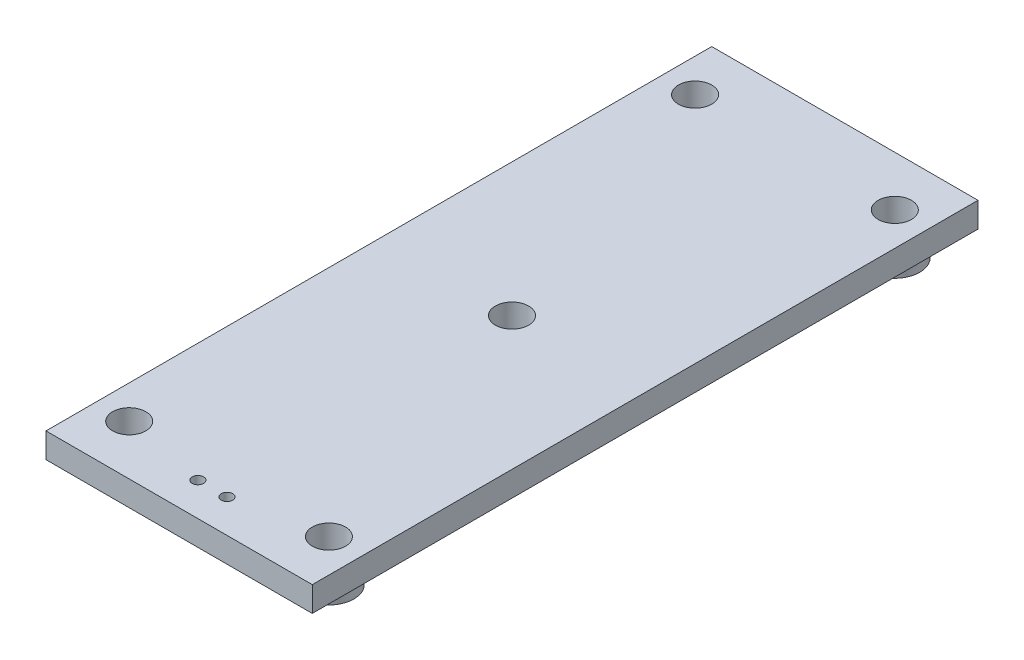
SolidWorks part; units mm, degrees
material "PW50:3:Ar:0:-1:C1:1:2:3:Re:11:"
ref_plane "front" through (0, 0, 0) normal (0, 0, 1) x (1, 0, 0)
ref_plane "top" through (0, 0, 0) normal (0, 1, 0) x (1, 0, 0)
ref_plane "side" through (0, 0, 0) normal (1, 0, 0) x (0, 0, -1)
sketch "Sketch1" plane through (0, 0, 0) normal (0, 1, 0) x (1, 0, 0)
  line L0 (101.6, 0) -> (-101.6, 0)
  line L1 (101.6, 0) -> (101.6, -508)
  line L2 (-101.6, -508) -> (101.6, -508)
  line L3 (-101.6, -508) -> (-101.6, 0)
  line L4 (0, 0) -> (0, -508) construction
  dimension "D1" = 508
  dimension "D2" = 203.2
extrude "Base-Extrude" add sketch "Sketch1" along normal blind 19.05
sketch "Sketch2" plane through (0, 0, 0) normal (0, -1, 0) x (1, 0, 0)
  line L0 (0, 508) -> (0, 254) construction
  line L1 (-101.6, 508) -> (101.6, 508) construction
  line L2 (101.6, 254) -> (0, 254) construction
  line L3 (101.6, 0) -> (101.6, 508) construction
  circle A0 centre (76.2, 469.9) radius 19.05
  circle A1 centre (76.2, 38.1) radius 19.05
  circle A2 centre (-76.2, 38.1) radius 19.05
  circle A3 centre (-76.2, 469.9) radius 19.05
  dimension "D2" = 38.1
  dimension "D1" = 38.1
  dimension "D3" = 152.4
extrude "Boss-Extrude1" add sketch "Sketch2" along normal blind 12.7
sketch "Sketch3" plane through (0, -12.7, 0) normal (0, -1, 0) x (1, 0, 0)
  circle A0 centre (76.2, 469.9) radius 12.7
  circle A2 centre (-76.2, 469.9) radius 12.7
  circle A3 centre (76.2, 38.1) radius 12.7
  circle A4 centre (-76.2, 38.1) radius 12.7
  circle A5 centre (-76.2, 38.1) radius 19.05 construction
  circle A6 centre (76.2, 38.1) radius 19.05 construction
  dimension "D1" = 25.4
extrude "Cut-Extrude1" cut sketch "Sketch3" against normal through all
sketch "Sketch4" plane through (0, 19.05, 0) normal (0, 1, 0) x (-1, 0, 0)
  line L0 (0, 254) -> (-101.6, 254) construction
  line L1 (-101.6, 0) -> (-101.6, 508) construction
  circle A0 centre (0, 254) radius 12.7
  dimension "D1" = 25.4
extrude "Cut-Extrude2" cut sketch "Sketch4" against normal through all
sketch "Sketch5" plane through (0, 0, 0) normal (0, -1, 0) x (1, 0, 0)
  circle A2 centre (11.1125, 482.6) radius 4.3656
  circle A3 centre (-11.1125, 482.6) radius 4.3656
  dimension "D1" = 8.7312
extrude "Cut-Extrude3" cut sketch "Sketch5" against normal through all
